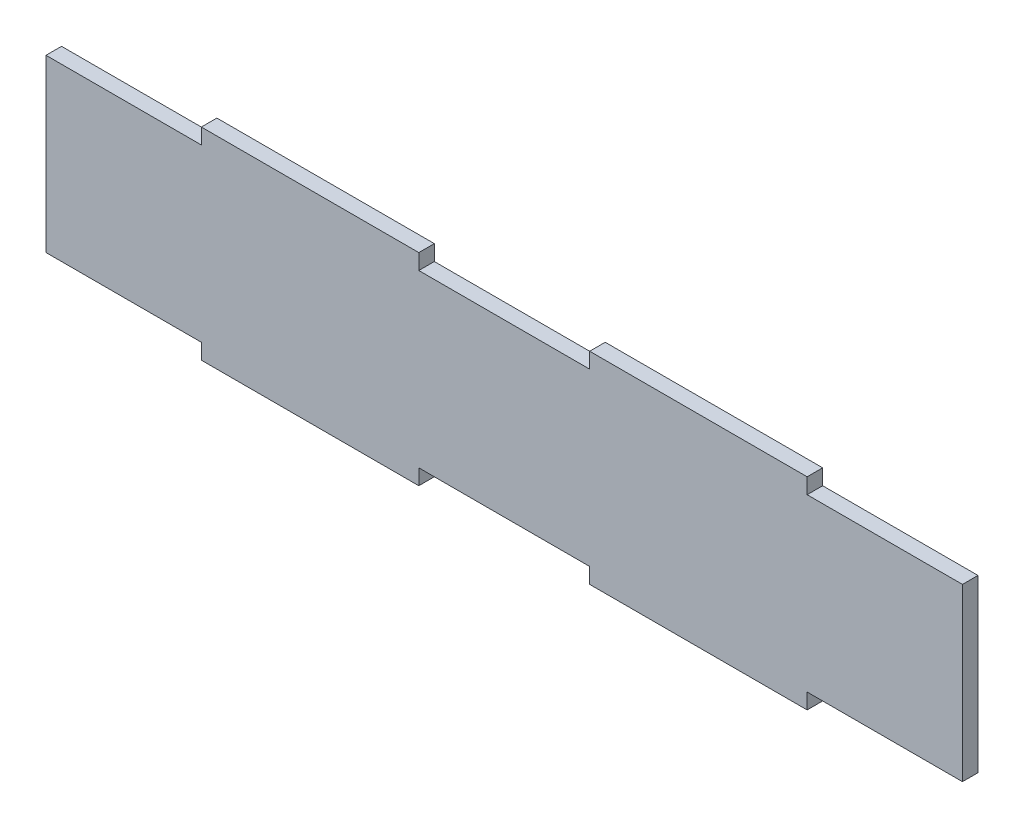
SolidWorks part; units mm, degrees
ref_plane "Front Plane" through (0, 0, 0) normal (0, 0, 1) x (1, 0, 0)
ref_plane "Top Plane" through (0, 0, 0) normal (0, 1, 0) x (1, 0, 0)
ref_plane "Right Plane" through (0, 0, 0) normal (1, 0, 0) x (0, 0, -1)
sketch "Sketch1" plane through (0, 0, 0) normal (0, 0, 1) x (1, 0, 0)
  line L0 (-147.5, 0) -> (-147.5, -31.4131) construction
  line L1 (0, 0) -> (-295, 0)
  line L2 (0, 0) -> (0, -55)
  line L3 (0, -55) -> (-295, -55)
  line L4 (-295, 0) -> (-295, -55)
  line L5 (-50, 0) -> (-120, 0)
  line L6 (-50, 0) -> (-50, 5)
  line L7 (-50, 5) -> (-120, 5)
  line L8 (-120, 0) -> (-120, 5)
  line L9 (0, -27.5) -> (-27.5506, -27.5) construction
  line L10 (-245, 5) -> (-175, 5)
  line L11 (-175, 0) -> (-175, 5)
  line L12 (-245, 0) -> (-175, 0)
  line L13 (-245, 0) -> (-245, 5)
  line L14 (-245, -55) -> (-245, -60)
  line L15 (-245, -55) -> (-175, -55)
  line L16 (-175, -55) -> (-175, -60)
  line L17 (-245, -60) -> (-175, -60)
  line L18 (-50, -60) -> (-120, -60)
  line L19 (-120, -55) -> (-120, -60)
  line L20 (-50, -55) -> (-120, -55)
  line L21 (-50, -55) -> (-50, -60)
  dimension "D1" = 55
  dimension "D2" = 295
  dimension "D3" = 70
  dimension "D4" = 5
  dimension "D5" = 50
extrude "Boss-Extrude1" add sketch "Sketch1" along normal blind 5 contours L1 L4 L3 L2 | L13 L1 L11 L10 | L14 L17 L16 L3 | L8 L1 L6 L7 | L21 L3 L19 L18
